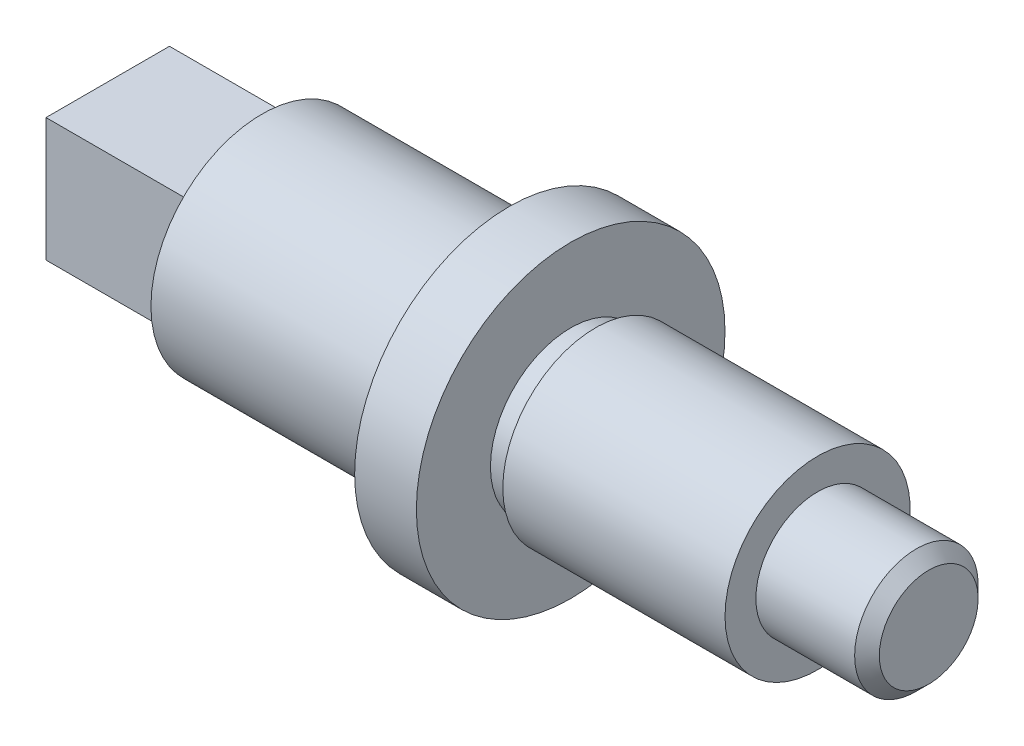
SolidWorks part; units mm, degrees
ref_plane "Ebene vorne" through (0, 0, 0) normal (0, 0, 1) x (1, 0, 0)
ref_plane "Ebene oben" through (0, 0, 0) normal (0, 1, 0) x (1, 0, 0)
ref_plane "Ebene rechts" through (0, 0, 0) normal (1, 0, 0) x (0, 0, -1)
sketch "Skizze1" plane through (0, 0, 0) normal (0, 0, 1) x (1, 0, 0)
  line L0 (0, 0) -> (221.8197, 0) construction
  line L1 (18.1874, 0) -> (18.1874, -18)
  line L2 (18.1874, -18) -> (54.1874, -18)
  line L3 (58.1874, -22) -> (58.1874, -25)
  line L4 (58.1874, -25) -> (68.1874, -25)
  line L5 (68.1874, -25) -> (68.1874, -13)
  line L6 (68.1874, -13) -> (72.1874, -13)
  line L7 (72.1874, -13) -> (72.1874, -15)
  line L8 (72.1874, -15) -> (108.1874, -15)
  line L9 (108.1874, -15) -> (108.1874, -10)
  line L10 (108.1874, -10) -> (124.1874, -10)
  line L11 (126.1874, -8) -> (126.1874, 0)
  line L12 (124.1874, -10) -> (126.1874, -8)
  line L13 (18.1874, 0) -> (126.1874, 0)
  arc A0 (58.1874, -22) -> (54.1874, -18) centre (54.1874, -22) ccw
  point P14 (126.1874, -10)
  point P17 (58.1874, -18)
  dimension "D11" = 4
  dimension "D1" = 18
  dimension "D2" = 25
  dimension "D3" = 13
  dimension "D4" = 15
  dimension "D5" = 10
  dimension "D6" = 18
  dimension "D7" = 36
  dimension "D8" = 4
  dimension "D9" = 10
  dimension "D10" = 40
revolve "Rotation1" add sketch "Skizze1" angle 360 about L0
sketch "Skizze2" plane through (18.1874, 0, 0) normal (-1, 0, 0) x (0, 0, 1)
  line L1 (-10, 10) -> (10, 10)
  line L2 (-10, 10) -> (-10, -10)
  line L3 (-10, -10) -> (10, -10)
  line L4 (10, 10) -> (10, -10)
  line L5 (-10, 10) -> (10, -10) construction
  line L6 (-10, -10) -> (10, 10) construction
  point P0 (0, 0)
  dimension "D1" = 20
  dimension "D2" = 20
extrude "Aufsatz-Linear austragen1" add sketch "Skizze2" along normal blind 25
